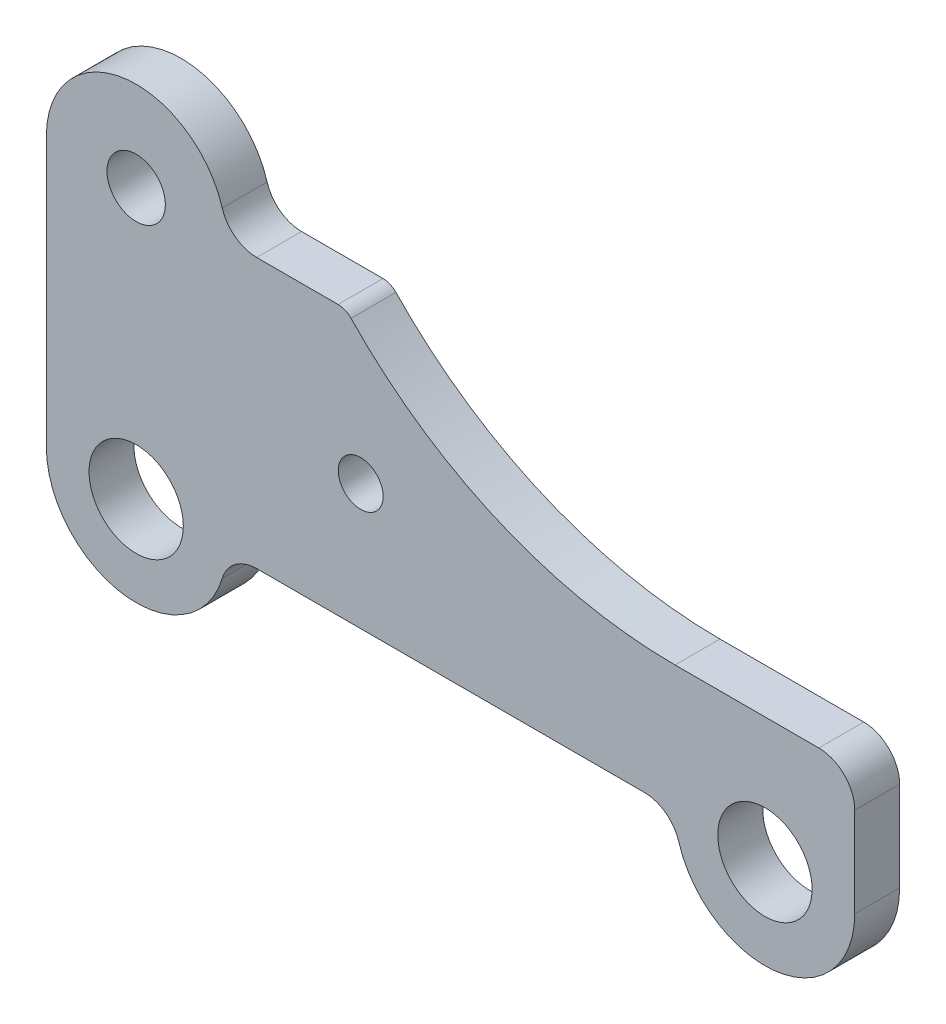
SolidWorks part; units mm, degrees
ref_plane "Front Plane" through (0, 0, 0) normal (0, 0, 1) x (1, 0, 0)
ref_plane "Top Plane" through (0, 0, 0) normal (0, 1, 0) x (1, 0, 0)
ref_plane "Right Plane" through (0, 0, 0) normal (1, 0, 0) x (0, 0, -1)
sketch "Sketch2" plane through (0, 0, 0) normal (0, 0, 1) x (1, 0, 0)
  line L0 (0, 0) -> (0, 40) construction
  line L1 (0, 0) -> (89.8411, 0) construction
  line L2 (10, 40) -> (10, 10) construction
  line L3 (10, 10) -> (89.092, 10) construction
  line L4 (0, 40) -> (0, 10)
  line L5 (23.4164, 10) -> (66.5836, 10)
  line L6 (90, 10) -> (90, 20)
  line L7 (86, 24) -> (70, 24)
  line L8 (32.4767, 40) -> (23.4164, 40)
  arc A0 (0, 10) -> (19.5831, 7.1429) centre (10, 10) ccw
  arc A1 (70.4169, 7.1429) -> (90, 10) centre (80, 10) ccw
  arc A2 (70, 24) -> (33.9199, 39.3846) centre (70, 74) cw
  arc A3 (0, 40) -> (19.5831, 42.8571) centre (10, 40) cw
  circle A4 centre (10, 40) radius 3.25
  circle A5 centre (10, 10) radius 5.25
  circle A6 centre (80, 10) radius 5.25
  circle A7 centre (35, 24) radius 2.5
  arc A8 (90, 20) -> (86, 24) centre (86, 20) ccw
  arc A9 (66.5836, 10) -> (70.4169, 7.1429) centre (66.5836, 6) cw
  arc A10 (19.5831, 7.1429) -> (23.4164, 10) centre (23.4164, 6) cw
  arc A11 (23.4164, 40) -> (19.5831, 42.8571) centre (23.4164, 44) cw
  arc A12 (33.9199, 39.3846) -> (32.4767, 40) centre (32.4767, 38) ccw
  point P24 (90, 24)
  point P27 (70, 10)
  point P30 (20, 10)
  point P33 (20, 40)
  dimension "D4" = 10
  dimension "D7" = 50
  dimension "D9" = 10
  dimension "D10" = 10.5
  dimension "D11" = 6.5
  dimension "D12" = 5
  dimension "D15" = 4
  dimension "D16" = 2
  dimension "D1" = 40
  dimension "D2" = 10
  dimension "D3" = 10
  dimension "D5" = 70
  dimension "D6" = 14
  dimension "D8" = 20
  dimension "D13" = 24
  dimension "D14" = 25
extrude "Boss-Extrude1" add sketch "Sketch2" along normal mid plane 5
